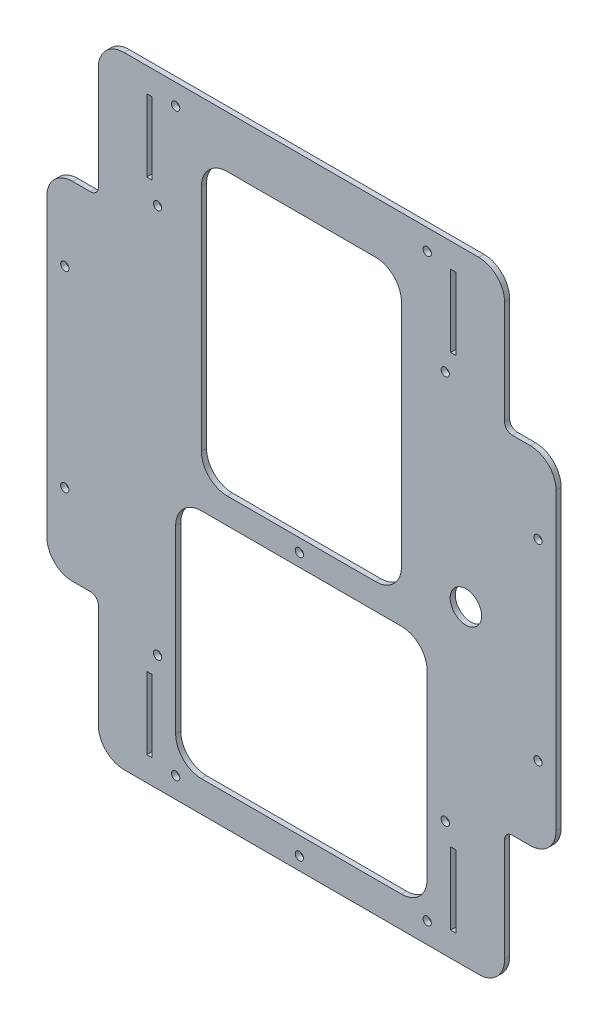
SolidWorks part; units mm, degrees
ref_plane "Ön Düzlem" through (0, 0, 0) normal (0, 0, 1) x (1, 0, 0)
ref_plane "Üst Düzlem" through (0, 0, 0) normal (0, 1, 0) x (1, 0, 0)
ref_plane "Sağ Düzlem" through (0, 0, 0) normal (1, 0, 0) x (0, 0, -1)
sketch "Çizim1" plane through (0, 0, 0) normal (0, 0, 1) x (1, 0, 0)
  line L0 (78.3978, 53) -> (78.3978, 58)
  line L1 (78.3978, 58) -> (-79.2022, 58)
  line L2 (-79.2022, 58) -> (-79.2022, 53)
  line L3 (-79.2022, 53) -> (-79.2022, 4.7)
  line L4 (-79.2022, 4.7) -> (-99.2022, 4.7)
  line L5 (-99.2022, 4.7) -> (-99.2022, -129.7)
  line L6 (-99.2022, -129.7) -> (-79.2022, -129.7)
  line L7 (-79.2022, -129.7) -> (-79.2022, -178)
  line L8 (-79.2022, -178) -> (-79.2022, -183)
  line L9 (-79.2022, -183) -> (78.3978, -183)
  line L10 (78.3978, -183) -> (78.3978, -178)
  line L11 (78.3978, -178) -> (78.3978, -129.7)
  line L12 (78.3978, -129.7) -> (98.3978, -129.7)
  line L13 (98.3978, -129.7) -> (98.3978, 4.7)
  line L14 (98.3978, 4.7) -> (78.3978, 4.7)
  line L15 (78.3978, 4.7) -> (78.3978, 53)
  dimension "D1" = 5
  dimension "D2" = 5
  dimension "D3" = 20
  dimension "D4" = 20
extrude "Yükseklik-Ekstrüzyon1" add sketch "Çizim1" along normal blind 2 contours L3 L4 L5 L6 L7 L8 L9 L10 L11 L12 L13 L14 L15 L0 L1 L2
fillet "Radyus1" radius 10 8 edges at (-79.2022, 58, 1) (-99.2022, 4.7, 1) (-99.2022, -129.7, 1) (-79.2022, -183, 1) (78.3978, -183, 1) (98.3978, -129.7, 1) (98.3978, 4.7, 1) (78.3978, 58, 1)
fillet "Radyus2" radius 3 4 edges at (-79.2022, -129.7, 1) (78.3978, -129.7, 1) (78.3978, 4.7, 1) (-79.2022, 4.7, 1)
sketch "Çizim2" plane through (0, 0, 0) normal (0, 0, -1) x (-1, 0, 0)
  line L0 (69.2022, -183) -> (-68.3978, -183) construction
  line L1 (-59.5978, -145.55) -> (-57.4978, -145.55)
  line L2 (-59.5978, -145.55) -> (-59.5978, -173.55)
  line L3 (-59.5978, -173.55) -> (-57.4978, -173.55)
  line L4 (-57.4978, -145.55) -> (-57.4978, -173.55)
  line L5 (-78.3978, -173) -> (-78.3978, -132.7) construction
  line L6 (0.4022, 58) -> (0.4022, -183) construction
  line L7 (-68.3978, 58) -> (69.2022, 58) construction
  line L8 (-98.3978, -62.5) -> (99.2022, -62.5) construction
  line L9 (-98.3978, -119.7) -> (-98.3978, -5.3) construction
  line L10 (99.2022, -5.3) -> (99.2022, -119.7) construction
  line L11 (58.3022, -145.55) -> (58.3022, -173.55)
  line L12 (60.4022, -173.55) -> (58.3022, -173.55)
  line L13 (60.4022, -145.55) -> (60.4022, -173.55)
  line L14 (60.4022, -145.55) -> (58.3022, -145.55)
  line L15 (60.4022, 20.55) -> (58.3022, 20.55)
  line L16 (60.4022, 20.55) -> (60.4022, 48.55)
  line L17 (60.4022, 48.55) -> (58.3022, 48.55)
  line L18 (58.3022, 20.55) -> (58.3022, 48.55)
  line L19 (-57.4978, 20.55) -> (-57.4978, 48.55)
  line L20 (-59.5978, 48.55) -> (-57.4978, 48.55)
  line L21 (-59.5978, 20.55) -> (-59.5978, 48.55)
  line L22 (-59.5978, 20.55) -> (-57.4978, 20.55)
  dimension "D1" = 2.1
  dimension "D2" = 9.45
  dimension "D3" = 18.8
  dimension "D4" = 28
extrude "Kes-Ekstrüzyon1" cut sketch "Çizim2" against normal blind 10
sketch "Çizim3" plane through (0, 0, 0) normal (0, 0, -1) x (-1, 0, 0)
  line L0 (69.2022, -183) -> (-68.3978, -183) construction
  line L1 (39.2022, -171) -> (-38.3978, -171)
  line L2 (49.2022, -161) -> (49.2022, -91)
  line L3 (39.2022, -81) -> (-38.3978, -81)
  line L4 (-48.3978, -161) -> (-48.3978, -91)
  line L5 (-98.3978, -119.7) -> (-98.3978, -5.3) construction
  line L6 (99.2022, -5.3) -> (99.2022, -119.7) construction
  arc A0 (49.2022, -91) -> (39.2022, -81) centre (39.2022, -91) ccw
  arc A1 (-38.3978, -81) -> (-48.3978, -91) centre (-38.3978, -91) ccw
  arc A2 (-38.3978, -171) -> (-48.3978, -161) centre (-38.3978, -161) cw
  arc A3 (39.2022, -171) -> (49.2022, -161) centre (39.2022, -161) ccw
  point P14 (-48.3978, -81)
  point P17 (-48.3978, -171)
  dimension "D5" = 10
  dimension "D1" = 12
  dimension "D2" = 50
  dimension "D3" = 50
  dimension "D4" = 90
extrude "Kes-Ekstrüzyon2" cut sketch "Çizim3" against normal blind 10
sketch "Çizim4" plane through (0, 0, 0) normal (0, 0, -1) x (-1, 0, 0)
  line L0 (39.2022, -81) -> (-38.3978, -81) construction
  line L1 (29.2022, -71) -> (-28.3978, -71)
  line L2 (39.2022, -61) -> (39.2022, 28)
  line L3 (29.2022, 38) -> (-28.3978, 38)
  line L4 (-38.3978, -61) -> (-38.3978, 28)
  line L5 (-98.3978, -119.7) -> (-98.3978, -5.3) construction
  line L6 (99.2022, -5.3) -> (99.2022, -119.7) construction
  line L7 (-68.3978, 58) -> (69.2022, 58) construction
  arc A0 (39.2022, 28) -> (29.2022, 38) centre (29.2022, 28) ccw
  arc A1 (-28.3978, 38) -> (-38.3978, 28) centre (-28.3978, 28) ccw
  arc A2 (-28.3978, -71) -> (-38.3978, -61) centre (-28.3978, -61) cw
  arc A3 (29.2022, -71) -> (39.2022, -61) centre (29.2022, -61) ccw
  dimension "D5" = 10
  dimension "D1" = 10
  dimension "D2" = 60
  dimension "D3" = 60
  dimension "D4" = 20
extrude "Kes-Ekstrüzyon3" cut sketch "Çizim4" against normal blind 10
sketch "Çizim5" plane through (0, 0, 0) normal (0, 0, -1) x (-1, 0, 0)
  line L0 (-98.3978, -119.7) -> (-98.3978, -5.3) construction
  line L1 (-68.3978, 58) -> (69.2022, 58) construction
  circle A0 centre (-63.3978, -62) radius 6.1
  dimension "D1" = 12.2
  dimension "D2" = 35
  dimension "D3" = 120
extrude "Kes-Ekstrüzyon4" cut sketch "Çizim5" against normal blind 10
sketch "Çizim6" plane through (0, 0, 0) normal (0, 0, -1) x (-1, 0, 0)
  line L0 (79.2022, -132.7) -> (79.2022, -173) construction
  line L1 (69.2022, -183) -> (-68.3978, -183) construction
  line L2 (99.2022, -5.3) -> (99.2022, -119.7) construction
  line L4 (99.2022, -62.5) -> (49.2022, -62.5) construction
  line L5 (89.2022, -129.7) -> (82.2022, -129.7) construction
  line L6 (99.2022, -5.3) -> (99.2022, -119.7) construction
  line L7 (0.4022, 58) -> (0.4022, 77.8983) construction
  line L8 (-68.3978, 58) -> (69.2022, 58) construction
  line L9 (-98.3978, -62.5) -> (-48.3978, -62.5) construction
  circle A0 centre (49.2022, -175) radius 1.6
  circle A1 centre (56.2022, -138) radius 1.6
  circle A2 centre (1.2022, -76) radius 1.6
  circle A3 centre (1.2022, -178) radius 1.6
  circle A4 centre (92.2022, -99.7) radius 1.6
  circle A5 centre (92.2022, -25.3) radius 1.6
  circle A6 centre (56.2022, 13) radius 1.6
  circle A7 centre (49.2022, 50) radius 1.6
  circle A8 centre (-48.3978, 50) radius 1.6
  circle A9 centre (-55.3978, 13) radius 1.6
  circle A10 centre (-91.3978, -25.3) radius 1.6
  circle A11 centre (-91.3978, -99.7) radius 1.6
  circle A12 centre (-55.3978, -138) radius 1.6
  circle A13 centre (-48.3978, -175) radius 1.6
  dimension "D1" = 30
  dimension "D2" = 8
  dimension "D3" = 3.2
  dimension "D4" = 23
  dimension "D5" = 45
  dimension "D6" = 107
  dimension "D8" = 5
  dimension "D9" = 30
  dimension "D7" = 98
  dimension "D10" = 7
extrude "Kes-Ekstrüzyon5" cut sketch "Çizim6" against normal blind 10
